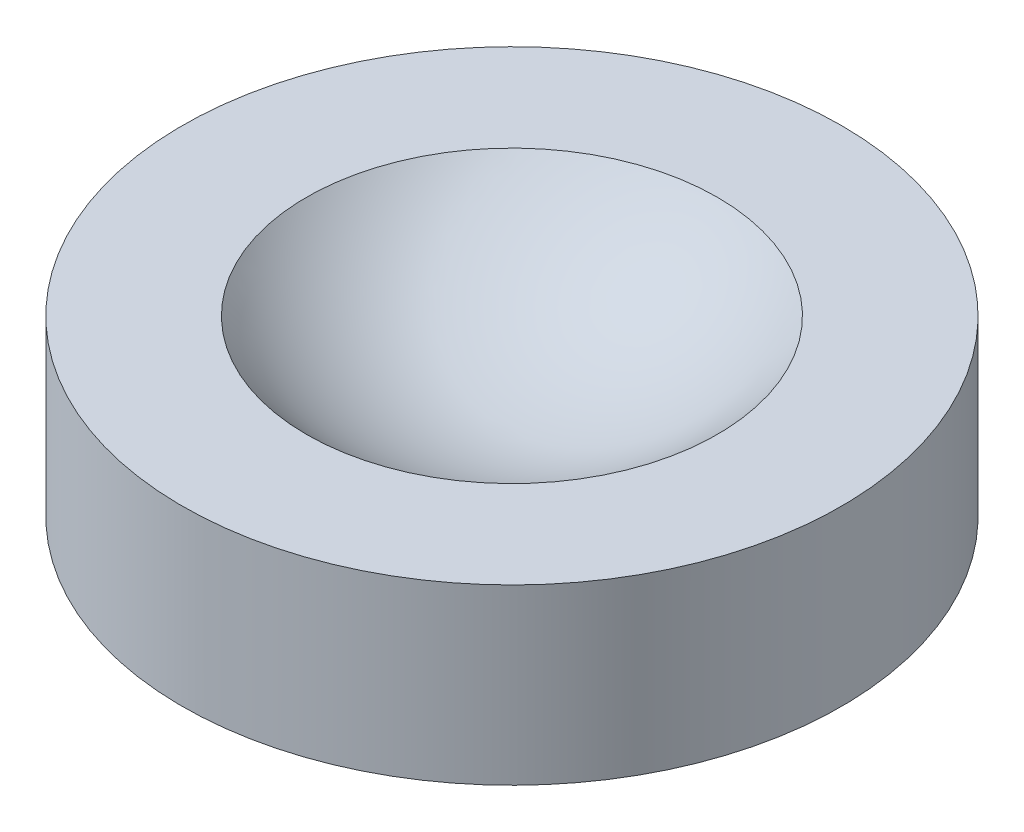
SolidWorks part; units mm, degrees
other "Fixed Steel Cup Liner 3"
other "Fixed Steel Cup Liner 3 Left"
ref_plane "Front Plane" through (0, 0, 0) normal (0, 0, 1) x (1, 0, 0)
ref_plane "Top Plane" through (0, 0, 0) normal (0, 1, 0) x (1, 0, 0)
ref_plane "Right Plane" through (0, 0, 0) normal (1, 0, 0) x (0, 0, -1)
sketch3d "Keyed Back Sketch datum points"
  point P0 (-56.2917, -69, 0)
  point P1 (-46.2917, -69, 0)
  point P2 (-56.2917, -69, 10)
ref_plane "Keyed Back Sketch plane" through (0, -69, 0) normal (0, -1, 0) x (-1, 0, 0)
sketch "Keyed Back Sketch" plane through (0, -69, 0) normal (0, -1, 0) x (-1, 0, 0)
  line L0 (74.8116, 27.4126) -> (70.7718, 29.745)
  arc A0 (70.7718, 29.745) -> (74.8116, 27.4126) centre (71.2917, 25.9808) ccw
extrude "Keyed Back" add sketch "Keyed Back Sketch" along normal blind 0.5 separate body
sketch3d "Cup Blank Sketch datum points"
  point P0 (-56.2917, -69.5, 0)
  point P1 (-46.2917, -69.5, 0)
  point P2 (-56.2917, -69.5, 10)
ref_plane "Cup Blank Sketch plane" through (0, -69.5, 0) normal (0, -1, 0) x (-1, 0, 0)
sketch "Cup Blank Sketch" plane through (0, -69.5, 0) normal (0, -1, 0) x (-1, 0, 0)
  circle A0 centre (71.2917, 25.9808) radius 3.8
extrude "Cup Blank" add sketch "Cup Blank Sketch" along normal blind 1.5
sketch3d "Spherical Bearing Seat axis line"
  line L0 (-71.2917, -73, -35.9808) -> (-71.2917, -73, -15.9808) construction
ref_axis "Spherical Bearing Seat axis" through (-71.2917, -73, -35.9808) along (0, 0, 1)
sketch3d "Spherical Bearing Seat profile datum points"
  point P0 (-71.2917, -73, -25.9808)
  point P1 (-61.2917, -73, -25.9808)
  point P2 (-71.2917, -73, -15.9808)
ref_plane "Spherical Bearing Seat profile plane" through (0, -73, 0) normal (0, -1, 0) x (-1, 0, 0)
sketch "Spherical Bearing Seat profile" plane through (0, -73, 0) normal (0, -1, 0) x (-1, 0, 0)
  line L0 (71.2917, 22.8808) -> (71.2917, 29.0808)
  arc A0 (71.2917, 29.0808) -> (71.2917, 22.8808) centre (71.2917, 25.9808) ccw
revolve "Spherical Bearing Seat" cut sketch "Spherical Bearing Seat profile" angle 360 about axis through (-71.2917, -73, -35.9808) along (0, 0, 1)
sketch3d "Mirror1 profile datum points"
  point P0 (0, 0, 0)
  point P1 (10, 0, 0)
  point P2 (0, 0, 10)
ref_plane "Mirror1 profile plane" through (0, 0, 0) normal (0, -1, 0) x (-1, 0, 0)
mirror "Mirror1" about plane through (0, 0, 0) normal (0, -1, 0) of bodies 103
delete or keep bodies "Remove1" type delete bodies bodies 103
